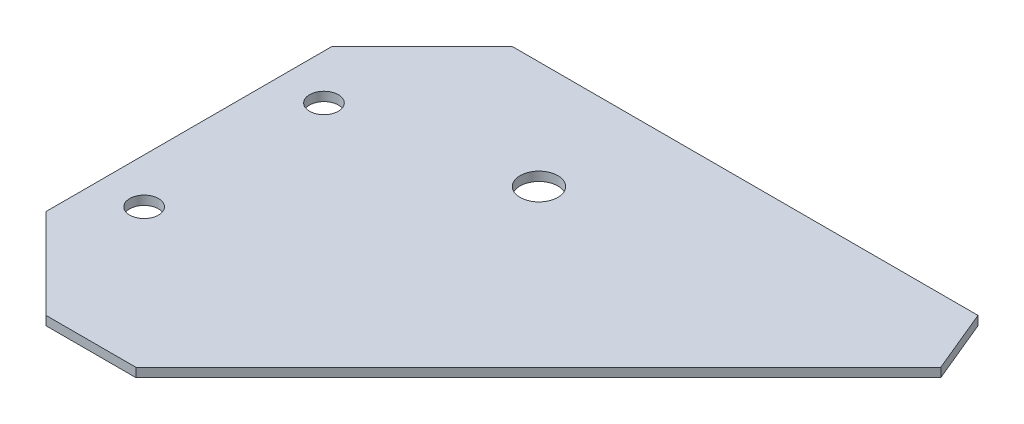
SolidWorks part; units mm, degrees
ref_plane "前视基准面" through (0, 0, 0) normal (0, 0, 1) x (1, 0, 0)
ref_plane "上视基准面" through (0, 0, 0) normal (0, 1, 0) x (1, 0, 0)
ref_plane "右视基准面" through (0, 0, 0) normal (1, 0, 0) x (0, 0, -1)
other "Configuration Table"
sketch "草图1" plane through (0, 0, 0) normal (0, 1, 0) x (1, 0, 0)
  line L3 (0, 0) -> (0, 31.8198)
  line L4 (0, 31.8198) -> (-31.8198, 31.8198) construction
  line L5 (-31.8198, 31.8198) -> (0, 0) construction
  line L6 (0, 31.8198) -> (80, 31.8198)
  line L7 (80, 31.8198) -> (80, 0)
  line L8 (80, 0) -> (0, 0)
  line L10 (0, 0) -> (80, 0)
  line L11 (0, 0) -> (0, -20)
  line L12 (0, -20) -> (80, -20)
  line L13 (80, 0) -> (80, -20)
  dimension "D1" = 45
  dimension "D2" = 80
  dimension "D3" = 20
extrude "凸台-拉伸1" add sketch "草图1" along normal blind 1 contours L8 L7 L6 L3 | L13 L8 L11 L12
sketch "草图3" plane through (0, 1, 0) normal (0, 1, 0) x (1, 0, 0)
  line L0 (80, -20) -> (80, 40)
  line L1 (80, 31.8198) -> (80, -20) construction
  line L2 (80, 40) -> (20, -20)
  line L3 (0, -20) -> (80, -20) construction
  line L4 (20, -20) -> (80, -20)
  dimension "D1" = 60
  dimension "D2" = 45
extrude "切除-拉伸1" cut sketch "草图3" against normal blind 10
chamfer "倒角1" distance 10 3 edges at (0, 0.5, -31.8198) (71.8198, 0.5, -31.8198) (0, 0.5, 20)
sketch "草图4" plane through (0, 1, 0) normal (0, 1, 0) x (1, 0, 0)
  line L0 (5, 15.9099) -> (5, -4.0901) construction
  line L1 (5, 5.9099) -> (0, 5.9099) construction
  line L2 (0, -10) -> (0, 21.8198) construction
  line L3 (10, 31.8198) -> (61.8198, 31.8198) construction
  circle A0 centre (5, 15.9099) radius 1.6
  circle A1 centre (5, -4.0901) radius 1.6
  circle A2 centre (25, 19.8198) radius 2.1
  dimension "D3" = 3.2
  dimension "D5" = 4.2
  dimension "D1" = 5
  dimension "D2" = 20
  dimension "D4" = 25
  dimension "D6" = 12
extrude "切除-拉伸2" cut sketch "草图4" against normal blind 10
